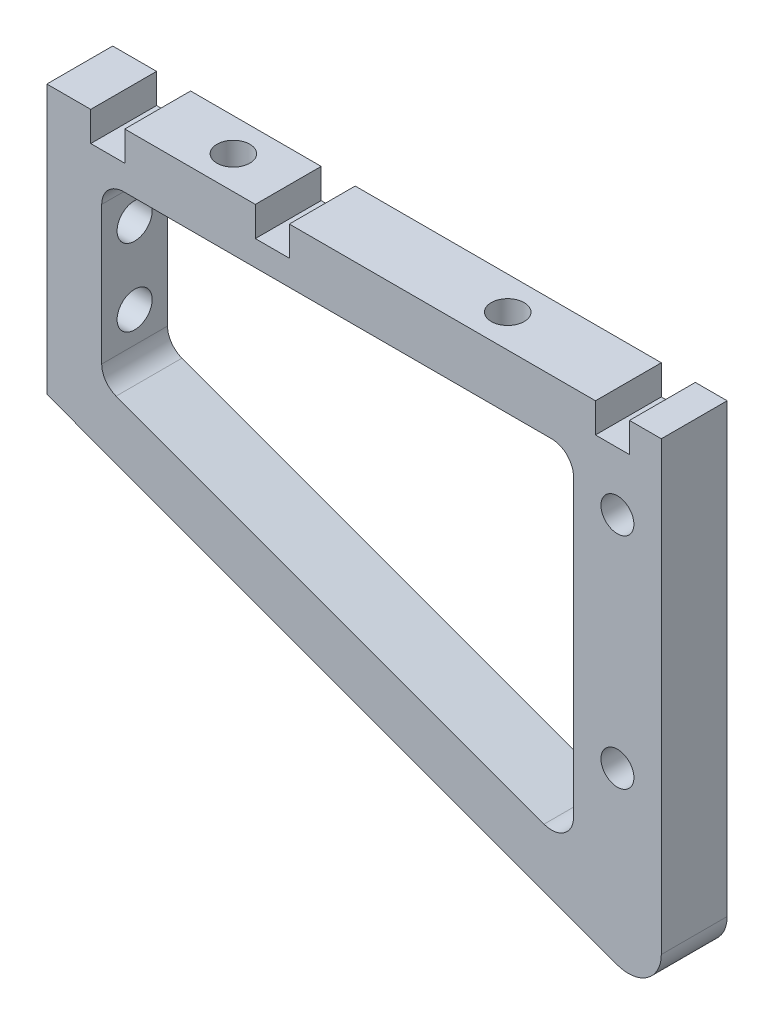
SolidWorks part; units mm, degrees
material "POM 乙缩醛共聚物"
ref_plane "前视基准面" through (0, 0, 0) normal (0, 0, 1) x (1, 0, 0)
ref_plane "上视基准面" through (0, 0, 0) normal (0, 1, 0) x (1, 0, 0)
ref_plane "右视基准面" through (0, 0, 0) normal (1, 0, 0) x (0, 0, -1)
sketch "草图1" plane through (0, 0, 0) normal (0, 0, 1) x (1, 0, 0)
  line L0 (0, 0) -> (0, 45)
  line L1 (0, 45) -> (-56, 45)
  line L2 (-56, 45) -> (-56, 20.5062) construction
  line L3 (-56, 20.5062) -> (0, 0) construction
  line L4 (-5, 7.1556) -> (-5, 40) construction
  line L5 (-5, 40) -> (-51, 40) construction
  line L6 (-51, 40) -> (-51, 24)
  line L7 (-51, 24) -> (-5, 7.1556) construction
  line L8 (-8, 40) -> (-8, 8.2541)
  line L9 (-51, 40) -> (-8, 40) construction
  line L10 (-51, 24) -> (-8, 8.2541) construction
  line L11 (-49, 40) -> (-45.846, 22.1127) construction
  line L12 (-49, 40) -> (-8, 40)
  line L13 (-8, 8.2541) -> (-45.846, 22.1127)
  line L14 (-56, 42.267) -> (-51.8981, 19.0042) construction
  line L15 (-51.8981, 19.0042) -> (0, 0)
  line L16 (-56, 42.267) -> (-56, 45)
  line L17 (-56, 42.267) -> (-56, 20.5062)
  line L18 (-56, 20.5062) -> (-51.8981, 19.0042)
  line L19 (-49, 40) -> (-51, 40)
  line L20 (-45.846, 22.1127) -> (-51, 24)
  circle A0 centre (-4, 37) radius 1.5
  circle A1 centre (-4, 17) radius 1.5
  dimension "D6" = 20
  dimension "D7" = 8
  dimension "D8" = 3
  dimension "D9" = 4
  dimension "D1" = 5
  dimension "D2" = 45
  dimension "D3" = 56
  dimension "D4" = 16
  dimension "D5" = 8
  dimension "D10" = 80
  dimension "D11" = 7
  dimension "D12" = 6.5
extrude "凸台-拉伸1" add sketch "草图1" along normal blind 6
fillet "圆角1" radius 3 1 edges at (0, 0, 3)
sketch "草图2" plane through (0, 45, 0) normal (0, 1, 0) x (1, 0, 0)
  line L0 (0, -3) -> (-42, -3) construction
  line L1 (0, -6) -> (0, 0) construction
  circle A0 centre (-17, -3) radius 1.5
  circle A1 centre (-42, -3) radius 1.5
  dimension "D1" = 25
  dimension "D2" = 3
  dimension "D3" = 17
extrude "切除-拉伸1" cut sketch "草图2" against normal up to next
sketch "草图3" plane through (0, 0, 6) normal (0, 0, 1) x (1, 0, 0)
  line L0 (0, 45) -> (-56, 45) construction
  line L1 (-52, 45) -> (-48.9, 45)
  line L2 (-52, 45) -> (-52, 42.3)
  line L3 (-52, 42.3) -> (-48.9, 42.3)
  line L4 (-48.9, 45) -> (-48.9, 42.3)
  line L14 (-37, 45) -> (-37, 42.3)
  line L15 (-37, 45) -> (-33.9, 45)
  line L16 (-33.9, 45) -> (-33.9, 42.3)
  line L17 (-37, 42.3) -> (-33.9, 42.3)
  line L22 (-6, 45) -> (-6, 42.3)
  line L23 (-6, 45) -> (-2.9, 45)
  line L24 (-2.9, 45) -> (-2.9, 42.3)
  line L25 (-6, 42.3) -> (-2.9, 42.3)
  line L26 (-56, 45) -> (-56, 20.5062) construction
  point P14 (-35.45, 42.3)
  point P15 (-50.45, 42.3)
  point P18 (-4.45, 42.3)
  dimension "D1" = 3.1
  dimension "D2" = 2.7
  dimension "D3" = 4
  dimension "D6" = 15
  dimension "D7" = 31
  dimension "D4" = 2
  dimension "D5" = 2
extrude "切除-拉伸2" cut sketch "草图3" against normal through all
fillet "圆角2" radius 2 4 edges at (-8, 8.2541, 3) (-8, 40, 3) (-51, 24, 3) (-51, 40, 3)
sketch "草图4" plane through (-51, 0, 0) normal (1, 0, 0) x (0, 0, -1)
  line L0 (-3, 38) -> (-3, 25.3975) construction
  line L1 (0, 38) -> (-6, 38) construction
  line L2 (-6, 25.3975) -> (0, 25.3975) construction
  line L3 (-6, 31.6988) -> (0, 31.6988) construction
  line L4 (-6, 38) -> (-6, 25.3975) construction
  line L5 (0, 38) -> (0, 25.3975) construction
  circle A0 centre (-3, 35.1988) radius 1.6
  circle A1 centre (-3, 28.1988) radius 1.6
  dimension "D1" = 3.2
  dimension "D2" = 7
extrude "切除-拉伸3" cut sketch "草图4" against normal through all
